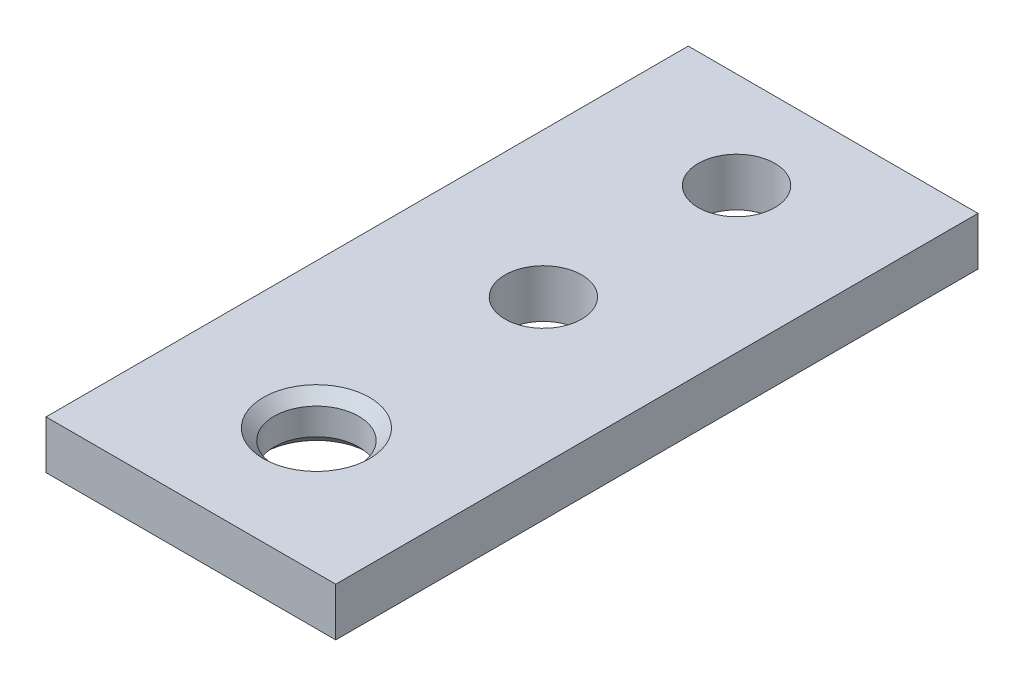
SolidWorks part; units mm, degrees
material "6061-T6 (SS)"
ref_plane "Front Plane" through (0, 0, 0) normal (0, 0, 1) x (1, 0, 0)
ref_plane "Top Plane" through (0, 0, 0) normal (0, 1, 0) x (1, 0, 0)
ref_plane "Right Plane" through (0, 0, 0) normal (1, 0, 0) x (0, 0, -1)
sketch "Sketch1" plane through (0, 0, 0) normal (0, 0, 1) x (1, 0, 0)
  line L1 (-19.05, -3.175) -> (19.05, -3.175)
  line L2 (-19.05, -3.175) -> (-19.05, 3.175)
  line L3 (-19.05, 3.175) -> (19.05, 3.175)
  line L4 (19.05, -3.175) -> (19.05, 3.175)
  line L5 (-19.05, -3.175) -> (19.05, 3.175) construction
  line L6 (-19.05, 3.175) -> (19.05, -3.175) construction
  point P0 (0, 0)
  dimension "D1" = 38.1
  dimension "D2" = 6.35
extrude "Extrude1" add sketch "Sketch1" along normal blind 84.455
sketch "Sketch2" plane through (0, 3.175, 0) normal (0, 1, 0) x (1, 0, 0)
  line L0 (0, 0) -> (0, -12.7) construction
  line L1 (19.05, 0) -> (-19.05, 0) construction
  line L2 (0, -12.7) -> (0, -38.1) construction
  line L3 (0, -38.1) -> (0, -67.945) construction
  line L4 (19.05, -84.455) -> (-19.05, -84.455) construction
  dimension "D1" = 12.7
  dimension "D2" = 38.1
  dimension "D3" = 16.51
hole_wizard "3/8 Clearance Hole1" positions "3DSketch1" profile "Sketch3" hole size "3/8" standard "Ansi Inch"
sketch3d "3DSketch1"
  point P0 (0, 3.175, 12.7)
  point P3 (0, 3.175, 38.1)
sketch "Sketch3" plane through (0, 3.175, 12.7) normal (1, 0, 0) x (0, 0, 1)
  line L0 (0, 0) -> (0, 19.0315)
  line L1 (0, 19.0315) -> (5.0419, 16.002)
  line L2 (5.0419, 16.002) -> (5.0419, 0)
  line L5 (5.0419, 0) -> (0, 0)
  line L10 (0, 19.0315) -> (-5.0419, 16.002) construction
  line L11 (0, -6.35) -> (0, 107.95) construction
  dimension "Hole Dia." = 10.0838
  dimension "Hole Depth" = 16.002
  dimension "Drill Angle" = 118
hole_wizard "7/16 (0.4375) Diameter Hole2" positions "3DSketch2" profile "Sketch4" hole size "7/16" standard "Ansi Inch" end condition through all
sketch3d "3DSketch2"
  point P0 (0, 3.175, 67.945)
sketch "Sketch4" plane through (0, 3.175, 67.945) normal (1, 0, 0) x (0, 0, 1)
  line L0 (0, 0) -> (0, 6.35)
  line L1 (0, 6.35) -> (6.985, 6.35)
  line L2 (5.5562, 4.9212) -> (5.5562, 1.4287)
  line L3 (5.5562, 1.4287) -> (6.985, 0)
  line L5 (6.985, 0) -> (0, 0)
  line L6 (-5.5562, 1.4287) -> (-6.985, 0) construction
  line L7 (6.985, 6.35) -> (5.5562, 4.9212)
  line L8 (-6.985, 6.35) -> (-5.5562, 4.9212) construction
  line L11 (0, -6.35) -> (0, 107.95) construction
  dimension "Thru Hole Dia." = 11.1125
  dimension "Thru Hole Depth" = 6.35
  dimension "Near C'Sink Dia." = 13.97
  dimension "Near C'Sink Angle" = 90
  dimension "Far C'Sink Dia." = 13.97
  dimension "Far C'Sink Angle" = 90
sketch "Sketch5" plane through (0, 3.175, 0) normal (0, 1, 0) x (1, 0, 0)
  line L0 (19.05, -84.455) -> (19.05, 0) construction
  line L1 (-12.2634, -80.7474) -> (19.05, -80.7474)
  line L2 (-12.2634, -80.7474) -> (-12.2634, -64.6781)
  line L3 (-12.2634, -64.6781) -> (19.05, -64.6781)
  line L4 (19.05, -80.7474) -> (19.05, -64.6781)
extrude "Extrude2" [suppressed] add sketch "Sketch5" along normal blind 5.08
